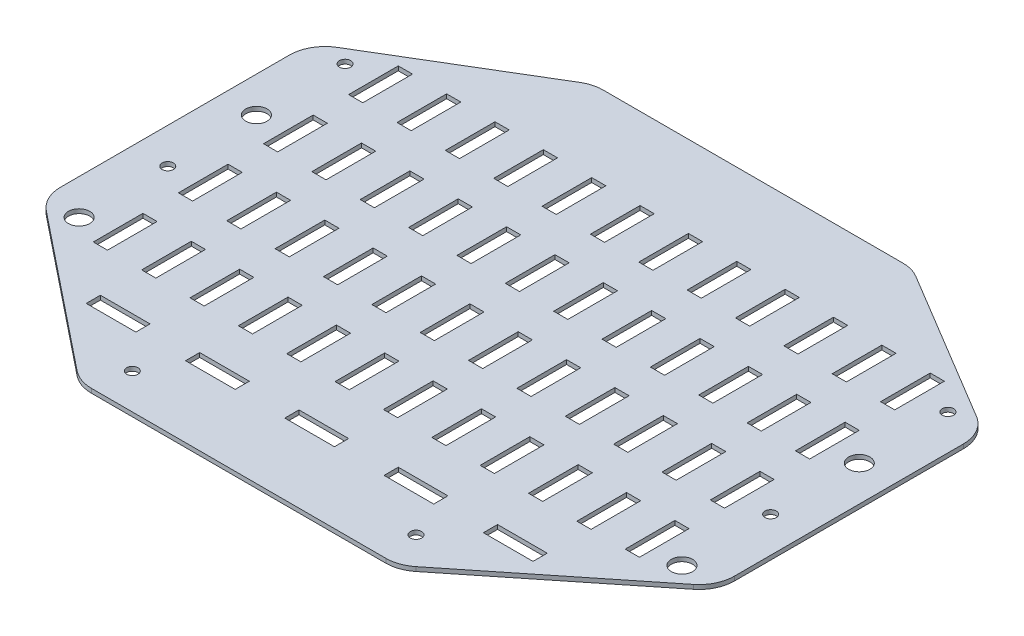
SolidWorks part; units mm, degrees
material "碳板"
ref_plane "前视基准面" through (0, 0, 0) normal (0, 0, 1) x (1, 0, 0)
ref_plane "上视基准面" through (0, 0, 0) normal (0, 1, 0) x (1, 0, 0)
ref_plane "右视基准面" through (0, 0, 0) normal (1, 0, 0) x (0, 0, -1)
sketch "草图1" plane through (0, 0, 0) normal (0, 1, 0) x (1, 0, 0)
  line L0 (95, 145) -> (95, 0) construction
  line L1 (0, 0) -> (190, 0)
  line L2 (0, 0) -> (0, 145)
  line L3 (0, 145) -> (190, 145)
  line L4 (190, 0) -> (190, 145)
  line L5 (10, 145) -> (10, 0) construction
  line L6 (0, 40) -> (50, 0)
  line L7 (0, 115) -> (50, 145)
  line L8 (190, 115) -> (140, 145)
  line L9 (190, 40) -> (140, 0)
  circle A0 centre (55, 10) radius 1.6
  circle A1 centre (135, 10) radius 1.6
  circle A2 centre (10, 40) radius 3
  circle A3 centre (10, 90) radius 3
  circle A4 centre (10, 65) radius 1.6
  circle A5 centre (10, 115) radius 1.6
  circle A6 centre (180, 40) radius 3
  circle A7 centre (180, 65) radius 1.6
  circle A8 centre (180, 90) radius 3
  circle A9 centre (180, 115) radius 1.6
  dimension "D3" = 3.2
  dimension "D7" = 6
  dimension "D9" = 50
  dimension "D10" = 3.2
  dimension "D12" = 50
  dimension "D1" = 190
  dimension "D2" = 145
  dimension "D4" = 80
  dimension "D5" = 10
  dimension "D6" = 10
  dimension "D8" = 40
  dimension "D11" = 65
  dimension "D13" = 40
  dimension "D14" = 50
  dimension "D15" = 30
extrude "凸台-拉伸1" add sketch "草图1" along normal blind 1.2 contours L9 L4 L8 L3 L7 L2 L6 L1 A8 A6 A5 A4 A3 A2 A0 A1 A7 A9
sketch "草图2" plane through (0, 1.2, 0) normal (0, 1, 0) x (1, 0, 0)
  line L0 (0, 115) -> (190, 115) construction
  line L1 (0, 40) -> (0, 115) construction
  line L2 (18, 122) -> (22, 122)
  line L3 (18, 122) -> (18, 108)
  line L4 (18, 108) -> (22, 108)
  line L5 (22, 122) -> (22, 108)
  line L6 (18, 122) -> (22, 108) construction
  line L7 (18, 108) -> (22, 122) construction
  line L8 (95, 145) -> (95, 0) construction
  line L9 (50, 145) -> (140, 145) construction
  line L10 (50, 0) -> (140, 0) construction
  line L11 (31.6364, 122) -> (31.6364, 108)
  line L12 (31.6364, 122) -> (35.6364, 122)
  line L13 (35.6364, 122) -> (35.6364, 108)
  line L14 (31.6364, 108) -> (35.6364, 108)
  line L15 (45.2727, 122) -> (45.2727, 108)
  line L16 (45.2727, 122) -> (49.2727, 122)
  line L17 (49.2727, 122) -> (49.2727, 108)
  line L18 (45.2727, 108) -> (49.2727, 108)
  line L19 (58.9091, 122) -> (58.9091, 108)
  line L20 (58.9091, 122) -> (62.9091, 122)
  line L21 (62.9091, 122) -> (62.9091, 108)
  line L22 (58.9091, 108) -> (62.9091, 108)
  line L23 (72.5455, 122) -> (72.5455, 108)
  line L24 (72.5455, 122) -> (76.5455, 122)
  line L25 (76.5455, 122) -> (76.5455, 108)
  line L26 (72.5455, 108) -> (76.5455, 108)
  line L27 (86.1818, 122) -> (86.1818, 108)
  line L28 (86.1818, 122) -> (90.1818, 122)
  line L29 (90.1818, 122) -> (90.1818, 108)
  line L30 (86.1818, 108) -> (90.1818, 108)
  line L31 (99.8182, 122) -> (99.8182, 108)
  line L32 (99.8182, 122) -> (103.8182, 122)
  line L33 (103.8182, 122) -> (103.8182, 108)
  line L34 (99.8182, 108) -> (103.8182, 108)
  line L35 (113.4545, 122) -> (113.4545, 108)
  line L36 (113.4545, 122) -> (117.4545, 122)
  line L37 (117.4545, 122) -> (117.4545, 108)
  line L38 (113.4545, 108) -> (117.4545, 108)
  line L39 (127.0909, 122) -> (127.0909, 108)
  line L40 (127.0909, 122) -> (131.0909, 122)
  line L41 (131.0909, 122) -> (131.0909, 108)
  line L42 (127.0909, 108) -> (131.0909, 108)
  line L43 (140.7273, 122) -> (140.7273, 108)
  line L44 (140.7273, 122) -> (144.7273, 122)
  line L45 (144.7273, 122) -> (144.7273, 108)
  line L46 (140.7273, 108) -> (144.7273, 108)
  line L47 (154.3636, 122) -> (154.3636, 108)
  line L48 (154.3636, 122) -> (158.3636, 122)
  line L49 (158.3636, 122) -> (158.3636, 108)
  line L50 (154.3636, 108) -> (158.3636, 108)
  line L51 (168, 122) -> (168, 108)
  line L52 (168, 122) -> (172, 122)
  line L53 (172, 122) -> (172, 108)
  line L54 (168, 108) -> (172, 108)
  line L55 (31.6364, 98) -> (31.6364, 84)
  line L56 (31.6364, 98) -> (35.6364, 98)
  line L57 (35.6364, 98) -> (35.6364, 84)
  line L58 (31.6364, 84) -> (35.6364, 84)
  line L59 (45.2727, 98) -> (45.2727, 84)
  line L60 (45.2727, 98) -> (49.2727, 98)
  line L61 (49.2727, 98) -> (49.2727, 84)
  line L62 (45.2727, 84) -> (49.2727, 84)
  line L63 (58.9091, 98) -> (58.9091, 84)
  line L64 (58.9091, 98) -> (62.9091, 98)
  line L65 (62.9091, 98) -> (62.9091, 84)
  line L66 (58.9091, 84) -> (62.9091, 84)
  line L67 (72.5455, 98) -> (72.5455, 84)
  line L68 (72.5455, 98) -> (76.5455, 98)
  line L69 (76.5455, 98) -> (76.5455, 84)
  line L70 (72.5455, 84) -> (76.5455, 84)
  line L71 (86.1818, 98) -> (86.1818, 84)
  line L72 (86.1818, 98) -> (90.1818, 98)
  line L73 (90.1818, 98) -> (90.1818, 84)
  line L74 (86.1818, 84) -> (90.1818, 84)
  line L75 (99.8182, 98) -> (99.8182, 84)
  line L76 (99.8182, 98) -> (103.8182, 98)
  line L77 (103.8182, 98) -> (103.8182, 84)
  line L78 (99.8182, 84) -> (103.8182, 84)
  line L79 (113.4545, 98) -> (113.4545, 84)
  line L80 (113.4545, 98) -> (117.4545, 98)
  line L81 (117.4545, 98) -> (117.4545, 84)
  line L82 (113.4545, 84) -> (117.4545, 84)
  line L83 (127.0909, 98) -> (127.0909, 84)
  line L84 (127.0909, 98) -> (131.0909, 98)
  line L85 (131.0909, 98) -> (131.0909, 84)
  line L86 (127.0909, 84) -> (131.0909, 84)
  line L87 (140.7273, 98) -> (140.7273, 84)
  line L88 (140.7273, 98) -> (144.7273, 98)
  line L89 (144.7273, 98) -> (144.7273, 84)
  line L90 (140.7273, 84) -> (144.7273, 84)
  line L91 (154.3636, 98) -> (154.3636, 84)
  line L92 (154.3636, 98) -> (158.3636, 98)
  line L93 (158.3636, 98) -> (158.3636, 84)
  line L94 (154.3636, 84) -> (158.3636, 84)
  line L95 (168, 98) -> (168, 84)
  line L96 (168, 98) -> (172, 98)
  line L97 (172, 98) -> (172, 84)
  line L98 (168, 84) -> (172, 84)
  line L99 (31.6364, 74) -> (31.6364, 60)
  line L100 (31.6364, 74) -> (35.6364, 74)
  line L101 (35.6364, 74) -> (35.6364, 60)
  line L102 (31.6364, 60) -> (35.6364, 60)
  line L103 (45.2727, 74) -> (45.2727, 60)
  line L104 (45.2727, 74) -> (49.2727, 74)
  line L105 (49.2727, 74) -> (49.2727, 60)
  line L106 (45.2727, 60) -> (49.2727, 60)
  line L107 (58.9091, 74) -> (58.9091, 60)
  line L108 (58.9091, 74) -> (62.9091, 74)
  line L109 (62.9091, 74) -> (62.9091, 60)
  line L110 (58.9091, 60) -> (62.9091, 60)
  line L111 (72.5455, 74) -> (72.5455, 60)
  line L112 (72.5455, 74) -> (76.5455, 74)
  line L113 (76.5455, 74) -> (76.5455, 60)
  line L114 (72.5455, 60) -> (76.5455, 60)
  line L115 (86.1818, 74) -> (86.1818, 60)
  line L116 (86.1818, 74) -> (90.1818, 74)
  line L117 (90.1818, 74) -> (90.1818, 60)
  line L118 (86.1818, 60) -> (90.1818, 60)
  line L119 (99.8182, 74) -> (99.8182, 60)
  line L120 (99.8182, 74) -> (103.8182, 74)
  line L121 (103.8182, 74) -> (103.8182, 60)
  line L122 (99.8182, 60) -> (103.8182, 60)
  line L123 (113.4545, 74) -> (113.4545, 60)
  line L124 (113.4545, 74) -> (117.4545, 74)
  line L125 (117.4545, 74) -> (117.4545, 60)
  line L126 (113.4545, 60) -> (117.4545, 60)
  line L127 (127.0909, 74) -> (127.0909, 60)
  line L128 (127.0909, 74) -> (131.0909, 74)
  line L129 (131.0909, 74) -> (131.0909, 60)
  line L130 (127.0909, 60) -> (131.0909, 60)
  line L131 (140.7273, 74) -> (140.7273, 60)
  line L132 (140.7273, 74) -> (144.7273, 74)
  line L133 (144.7273, 74) -> (144.7273, 60)
  line L134 (140.7273, 60) -> (144.7273, 60)
  line L135 (154.3636, 74) -> (154.3636, 60)
  line L136 (154.3636, 74) -> (158.3636, 74)
  line L137 (158.3636, 74) -> (158.3636, 60)
  line L138 (154.3636, 60) -> (158.3636, 60)
  line L139 (168, 74) -> (168, 60)
  line L140 (168, 74) -> (172, 74)
  line L141 (172, 74) -> (172, 60)
  line L142 (168, 60) -> (172, 60)
  line L143 (31.6364, 50) -> (31.6364, 36)
  line L144 (31.6364, 50) -> (35.6364, 50)
  line L145 (35.6364, 50) -> (35.6364, 36)
  line L146 (31.6364, 36) -> (35.6364, 36)
  line L147 (45.2727, 50) -> (45.2727, 36)
  line L148 (45.2727, 50) -> (49.2727, 50)
  line L149 (49.2727, 50) -> (49.2727, 36)
  line L150 (45.2727, 36) -> (49.2727, 36)
  line L151 (58.9091, 50) -> (58.9091, 36)
  line L152 (58.9091, 50) -> (62.9091, 50)
  line L153 (62.9091, 50) -> (62.9091, 36)
  line L154 (58.9091, 36) -> (62.9091, 36)
  line L155 (72.5455, 50) -> (72.5455, 36)
  line L156 (72.5455, 50) -> (76.5455, 50)
  line L157 (76.5455, 50) -> (76.5455, 36)
  line L158 (72.5455, 36) -> (76.5455, 36)
  line L159 (86.1818, 50) -> (86.1818, 36)
  line L160 (86.1818, 50) -> (90.1818, 50)
  line L161 (90.1818, 50) -> (90.1818, 36)
  line L162 (86.1818, 36) -> (90.1818, 36)
  line L163 (99.8182, 50) -> (99.8182, 36)
  line L164 (99.8182, 50) -> (103.8182, 50)
  line L165 (103.8182, 50) -> (103.8182, 36)
  line L166 (99.8182, 36) -> (103.8182, 36)
  line L167 (113.4545, 50) -> (113.4545, 36)
  line L168 (113.4545, 50) -> (117.4545, 50)
  line L169 (117.4545, 50) -> (117.4545, 36)
  line L170 (113.4545, 36) -> (117.4545, 36)
  line L171 (127.0909, 50) -> (127.0909, 36)
  line L172 (127.0909, 50) -> (131.0909, 50)
  line L173 (131.0909, 50) -> (131.0909, 36)
  line L174 (127.0909, 36) -> (131.0909, 36)
  line L175 (140.7273, 50) -> (140.7273, 36)
  line L176 (140.7273, 50) -> (144.7273, 50)
  line L177 (144.7273, 50) -> (144.7273, 36)
  line L178 (140.7273, 36) -> (144.7273, 36)
  line L179 (154.3636, 50) -> (154.3636, 36)
  line L180 (154.3636, 50) -> (158.3636, 50)
  line L181 (158.3636, 50) -> (158.3636, 36)
  line L182 (154.3636, 36) -> (158.3636, 36)
  line L183 (168, 50) -> (168, 36)
  line L184 (168, 50) -> (172, 50)
  line L185 (172, 50) -> (172, 36)
  line L186 (168, 36) -> (172, 36)
  line L187 (18, 98) -> (18, 84)
  line L188 (18, 98) -> (22, 98)
  line L189 (22, 98) -> (22, 84)
  line L190 (18, 84) -> (22, 84)
  line L191 (18, 74) -> (18, 60)
  line L192 (18, 74) -> (22, 74)
  line L193 (22, 74) -> (22, 60)
  line L194 (18, 60) -> (22, 60)
  line L195 (18, 50) -> (18, 36)
  line L196 (18, 50) -> (22, 50)
  line L197 (22, 50) -> (22, 36)
  line L198 (18, 36) -> (22, 36)
  line L199 (18, 122) -> (18, 98) construction
  line L200 (25, 20) -> (165, 20) construction
  line L201 (0, 40) -> (50, 0) construction
  line L202 (190, 40) -> (140, 0) construction
  line L203 (60, 24) -> (60, 20)
  line L204 (32, 24) -> (46, 24)
  line L205 (32, 24) -> (32, 20)
  line L206 (32, 20) -> (46, 20)
  line L207 (46, 24) -> (46, 20)
  line L208 (32, 24) -> (46, 20) construction
  line L209 (32, 20) -> (46, 24) construction
  line L210 (60, 24) -> (74, 24)
  line L211 (74, 24) -> (74, 20)
  line L212 (60, 20) -> (74, 20)
  line L213 (88, 24) -> (88, 20)
  line L214 (88, 24) -> (102, 24)
  line L215 (102, 24) -> (102, 20)
  line L216 (88, 20) -> (102, 20)
  line L217 (116, 24) -> (116, 20)
  line L218 (116, 24) -> (130, 24)
  line L219 (130, 24) -> (130, 20)
  line L220 (116, 20) -> (130, 20)
  line L221 (144, 24) -> (144, 20)
  line L222 (144, 24) -> (158, 24)
  line L223 (158, 24) -> (158, 20)
  line L224 (144, 20) -> (158, 20)
  point P4 (20, 115)
  point P213 (39, 22)
  point P220 (60, 22)
  dimension "D1" = 4
  dimension "D2" = 14
  dimension "D3" = 20
  dimension "D4" = 12
  dimension "D6" = 24
  dimension "D7" = 20
  dimension "D8" = 4
  dimension "D9" = 14
  dimension "D11" = 14
  dimension "D5" = 4
  dimension "D10" = 5
extrude "切除-拉伸1" cut sketch "草图2" against normal through all
fillet "圆角1" radius 10 8 edges at (140, 0.6, 0) (50, 0.6, 0) (0, 0.6, -40) (0, 0.6, -115) (140, 0.6, -145) (190, 0.6, -115) (190, 0.6, -40) (50, 0.6, -145)
